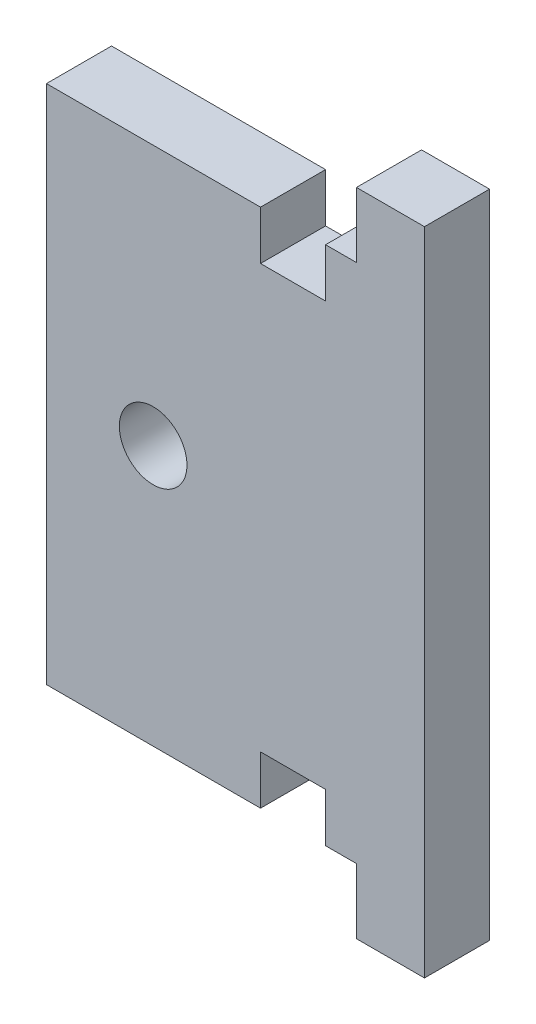
SolidWorks part; units mm, degrees
material "AISI 4130 Steel, annealed at 865C"
ref_plane "X-Y Datum" through (0, 0, 0) normal (0, 0, 1) x (1, 0, 0)
ref_plane "X-Z Datum" through (0, 0, 0) normal (0, 1, 0) x (1, 0, 0)
ref_plane "Y-Z Datum" through (0, 0, 0) normal (1, 0, 0) x (0, 0, -1)
sketch "Sketch2" plane through (0, 0, 0) normal (0, 0, 1) x (1, 0, 0)
  line L0 (34.925, 127) -> (0, 127) construction
  line L1 (0, 0) -> (43.942, 0)
  line L2 (0, 0) -> (0, 127)
  line L3 (0, 127) -> (43.942, 127)
  line L4 (43.942, 0) -> (43.942, 127)
  point P7 (17.4625, 31.75)
  point P8 (17.4625, 95.25)
  dimension "D1" = 43.942
extrude "Boss-Extrude1" add sketch "Sketch2" along normal blind 6.35
hole_wizard "M6 Clearance Hole1" positions "Sketch3" profile "Sketch4" hole size "M6" standard "ANSI Metric" end condition through all
sketch "Sketch3" plane through (0, 0, 6.35) normal (0, 0, 1) x (1, 0, 0)
  point P0 (17.4625, 31.75)
  point P3 (17.4625, 95.25)
sketch "Sketch4" plane through (17.4625, 31.75, 6.35) normal (1, 0, 0) x (0, -1, 0)
  line L0 (0, 0) -> (0, 6.35)
  line L1 (0, 6.35) -> (3.3, 6.35)
  line L2 (3.3, 6.35) -> (3.3, 0)
  line L5 (3.3, 0) -> (0, 0)
  line L11 (0, -6.35) -> (0, 107.95) construction
  dimension "Thru Hole Dia." = 6.6
  dimension "Thru Hole Depth" = 6.35
sketch "Sketch5" plane through (0, 0, 6.35) normal (0, 0, 1) x (1, 0, 0)
  line L0 (7.0505, 127) -> (7.0505, 0)
  line L1 (43.942, 127) -> (0, 127) construction
  line L2 (0, 0) -> (43.942, 0) construction
  circle A0 centre (17.4625, 95.25) radius 3.3 construction
  point P6 (14.1625, 95.25)
  line M4 (0, 127) -> (0, 0)
  line M5 (0, 0) -> (43.942, 0)
  line M7 (43.942, 127) -> (0, 127)
  dimension "D1" = 7.112
extrude "Cut-Extrude1" cut sketch "Sketch5" against normal through all and the other way through all contours L0 M7 M4 M5
sketch "Sketch6" plane through (0, 0, 6.35) normal (0, 0, 1) x (1, 0, 0)
  line L0 (-3.175, 120.65) -> (38.1, 120.65)
  line L1 (38.1, 120.65) -> (38.1, 130.175)
  line L2 (38.1, 130.175) -> (-3.175, 130.175)
  line L3 (-3.175, 130.175) -> (-3.175, 120.65)
  line L4 (0, 123.825) -> (34.925, 123.825)
  line L5 (34.925, 123.825) -> (34.925, 127)
  line L6 (34.925, 127) -> (0, 127)
  line L7 (0, 127) -> (0, 123.825)
  line L8 (0, 123.825) -> (34.925, 123.825)
  line L9 (34.925, 123.825) -> (34.925, 127)
  line L10 (34.925, 127) -> (0, 127)
  line L11 (0, 127) -> (0, 123.825)
  line L12 (0, 60.325) -> (34.925, 60.325)
  line L13 (34.925, 60.325) -> (34.925, 63.5)
  line L14 (34.925, 63.5) -> (0, 63.5)
  line L15 (0, 63.5) -> (0, 60.325)
  line L16 (0, 60.325) -> (34.925, 60.325)
  line L17 (34.925, 60.325) -> (34.925, 63.5)
  line L18 (34.925, 63.5) -> (0, 63.5)
  line L19 (0, 63.5) -> (0, 60.325)
  line L24 (0, 0) -> (34.925, 0)
  line L25 (34.925, 0) -> (34.925, 3.175)
  line L26 (34.925, 3.175) -> (0, 3.175)
  line L27 (0, 3.175) -> (0, 0)
  line L28 (38.1, 66.675) -> (-3.175, 66.675)
  line L29 (-3.175, 66.675) -> (-3.175, 57.15)
  line L30 (-3.175, 57.15) -> (38.1, 57.15)
  line L31 (38.1, 57.15) -> (38.1, 66.675)
  line L32 (38.1, 6.35) -> (-3.175, 6.35)
  line L33 (-3.175, 6.35) -> (-3.175, -3.175)
  line L34 (-3.175, -3.175) -> (38.1, -3.175)
  line L35 (38.1, -3.175) -> (38.1, 6.35)
  line L36 (37.3062, 127) -> (37.3063, 0)
  line L37 (43.942, 127) -> (7.0505, 127) construction
  line L38 (7.0505, 0) -> (43.942, 0) construction
  line M19 (7.0505, 127) -> (7.0505, 0)
  line M20 (7.0505, 0) -> (43.942, 0)
  line M22 (43.942, 127) -> (7.0505, 127)
  dimension "D5" = 2.3813
  dimension "D1" = 0
  dimension "D2" = 0
  dimension "D4" = 3.175
extrude "Cut-Extrude2" cut sketch "Sketch6" against normal through all contours L36 L9 L8 L0 M22 M19 | L8 L9 M22 M19 | L36 L28 L18 L17 L16 L30 M19 | L17 L18 L16 M19 | L36 L32 L26 L25 M19 M20 | L25 L26 M19 M20
sketch "Sketch7" plane through (0, 0, 6.35) normal (0, 0, 1) x (1, 0, 0)
  line L18 (34.29, 120.65) -> (27.94, 120.65)
  line L19 (34.29, 120.65) -> (34.29, 115.8875)
  line L20 (34.29, 115.8875) -> (27.94, 115.8875)
  line L21 (27.94, 120.65) -> (27.94, 115.8875)
  line L22 (34.29, 71.4375) -> (27.94, 71.4375)
  line L23 (34.29, 71.4375) -> (34.29, 66.675)
  line L24 (34.29, 66.675) -> (27.94, 66.675)
  line L25 (27.94, 71.4375) -> (27.94, 66.675)
  line L26 (34.29, 57.15) -> (27.94, 57.15)
  line L27 (34.29, 57.15) -> (34.29, 52.3875)
  line L28 (34.29, 52.3875) -> (27.94, 52.3875)
  line L29 (27.94, 57.15) -> (27.94, 52.3875)
  line L30 (34.29, 11.1125) -> (27.94, 11.1125)
  line L31 (34.29, 11.1125) -> (34.29, 6.35)
  line L32 (34.29, 6.35) -> (27.94, 6.35)
  line L33 (27.94, 11.1125) -> (27.94, 6.35)
  point P6 (0, 0)
extrude "Cut-Extrude3" cut sketch "Sketch7" against normal through all
sketch "Sketch8" plane through (0, 0, 6.35) normal (0, 0, 1) x (1, 0, 0)
  line L0 (34.925, 63.5) -> (43.942, 63.5)
  line L1 (43.942, 0) -> (43.942, 127) construction
  circle M3 centre (17.4625, 95.25) radius 3.3
  line M4 (37.3062, 120.65) -> (34.29, 120.65)
  line M5 (34.29, 120.65) -> (34.29, 115.8875)
  line M6 (34.29, 115.8875) -> (27.94, 115.8875)
  line M7 (27.94, 115.8875) -> (27.94, 120.65)
  line M8 (27.94, 120.65) -> (7.0505, 120.65)
  line M9 (7.0505, 120.65) -> (7.0505, 66.675)
  line M10 (7.0505, 66.675) -> (27.94, 66.675)
  line M11 (27.94, 66.675) -> (27.94, 71.4375)
  line M12 (27.94, 71.4375) -> (34.29, 71.4375)
  line M13 (34.29, 71.4375) -> (34.29, 66.675)
  line M14 (34.29, 66.675) -> (37.3062, 66.675)
  line M15 (37.3062, 66.675) -> (37.3062, 57.15)
  line M29 (43.942, 0) -> (43.942, 127)
  line M30 (43.942, 127) -> (37.3062, 127)
  line M31 (37.3062, 127) -> (37.3062, 120.65)
extrude "Cut-Extrude4" cut sketch "Sketch8" against normal through all and the other way through all contours L0 M15 M29 M30 M31 M4 M5 M6 M7 M8 M9 M10 M11 M12 M13 M14 M3
